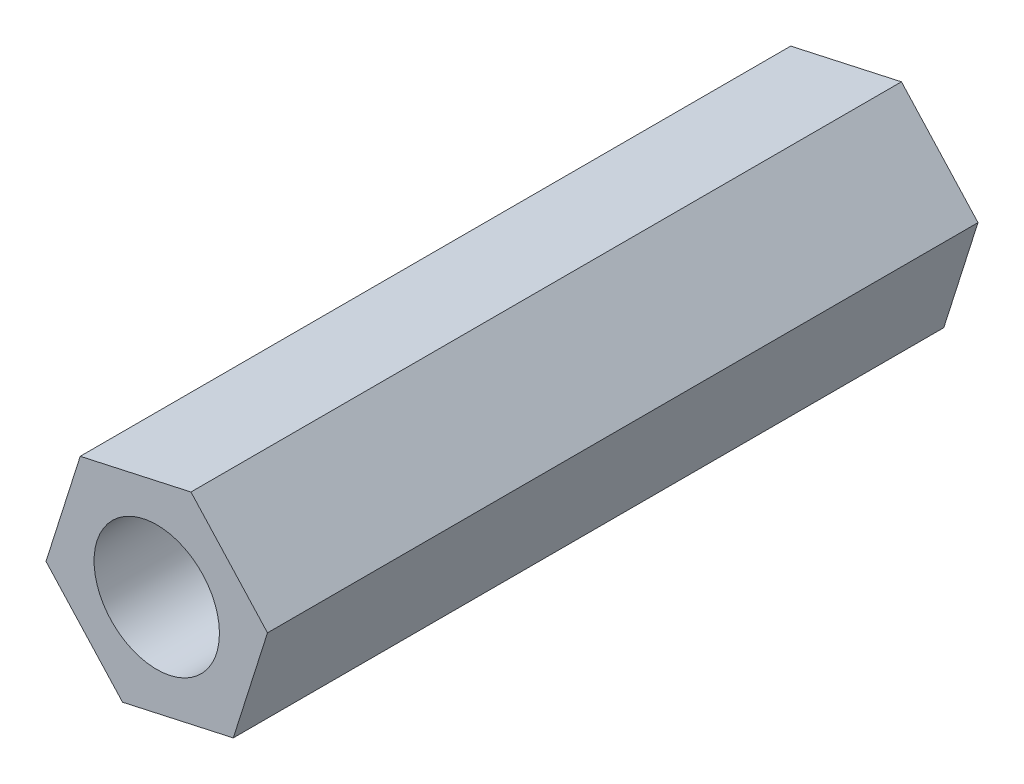
SolidWorks part; units mm, degrees
ref_plane "前视基准面" through (0, 0, 0) normal (0, 0, 1) x (1, 0, 0)
ref_plane "上视基准面" through (0, 0, 0) normal (0, 1, 0) x (1, 0, 0)
ref_plane "右视基准面" through (0, 0, 0) normal (1, 0, 0) x (0, 0, -1)
sketch "草图1" plane through (0, 0, 0) normal (0, 0, 1) x (1, 0, 0)
  line L1 (2.6498, 0.5847) -> (0.8185, 2.5871)
  line L2 (0.8185, 2.5871) -> (-1.8313, 2.0024)
  line L3 (-1.8313, 2.0024) -> (-2.6498, -0.5847)
  line L4 (-2.6498, -0.5847) -> (-0.8185, -2.5871)
  line L5 (-0.8185, -2.5871) -> (1.8313, -2.0024)
  line L6 (1.8313, -2.0024) -> (2.6498, 0.5847)
  circle A0 centre (0, 0) radius 2.35 construction
  circle A1 centre (0, 0) radius 1.5
extrude "凸台-拉伸1" add sketch "草图1" along normal blind 17
